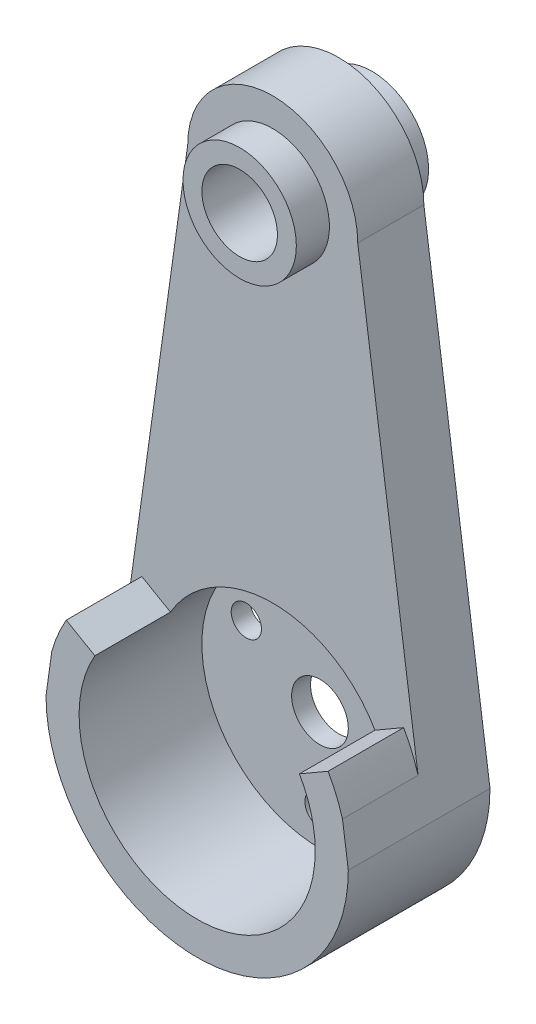
SolidWorks part; units mm, degrees
ref_plane "Plan de face" through (0, 0, 0) normal (0, 0, 1) x (1, 0, 0)
ref_plane "Plan de dessus" through (0, 0, 0) normal (0, 1, 0) x (1, 0, 0)
ref_plane "Plan de droite" through (0, 0, 0) normal (1, 0, 0) x (0, 0, -1)
sketch "Esquisse1" plane through (0, 0, 0) normal (0, 0, 1) x (1, 0, 0)
  line L0 (-16.3093, 0) -> (24.5372, 0) construction
  line L1 (9, 0) -> (16, -50)
  line L2 (-9, 0) -> (-16, -50)
  line L3 (-16, -50) -> (16, -50) construction
  line L4 (0, 0) -> (0, -50) construction
  arc A0 (-9, 0) -> (9, 0) centre (0, 0) cw
  arc A1 (-16, -50) -> (16, -50) centre (0, -50) ccw
  dimension "D1" = 9
  dimension "D2" = 16
  dimension "D3" = 50
extrude "Boss.-Extru.1" add sketch "Esquisse1" along normal blind 7
sketch "Esquisse2" plane through (0, 0, 7) normal (0, 0, 1) x (1, 0, 0)
  line L0 (0, 0) -> (0, -66) construction
  line L1 (16, -50) -> (-16, -50) construction
  circle A0 centre (0, -50) radius 3
  arc A1 (-16, -50) -> (16, -50) centre (0, -50) ccw construction
  dimension "D1" = 6
extrude "Enlèv. mat.-Extru.1" cut sketch "Esquisse2" against normal blind 7
sketch "Esquisse3" plane through (0, 0, 7) normal (0, 0, 1) x (1, 0, 0)
  line L0 (0, -50) -> (0, 0) construction
  line L1 (0, -50) -> (7.7942, -45.5) construction
  line L2 (0, -50) -> (-7.7942, -45.5) construction
  line L3 (0, -50) -> (0, -59) construction
  circle A3 centre (0, -59) radius 1.6
  circle A4 centre (-7.7942, -45.5) radius 1.6
  circle A5 centre (7.7942, -45.5) radius 1.6
  dimension "D5" = 9
  dimension "D6" = 9
extrude "Enlèv. mat.-Extru.2" cut sketch "Esquisse3" against normal blind 7
ref_plane "Plan1" through (0, 10, 0) normal (0, 1, 0) x (1, 0, 0)
sketch "Esquisse5" plane through (0, 0, 7) normal (0, 0, 1) x (1, 0, 0)
  circle A0 centre (0, -50) radius 12.5
  dimension "D1" = 25
extrude "Enlèv. mat.-Extru.5" cut sketch "Esquisse5" against normal blind 5
sketch "Esquisse16" plane through (0, 0, 0) normal (0, 0, -1) x (-1, 0, 0)
  circle A0 centre (0, 0) radius 6
  circle A1 centre (0, 0) radius 4
extrude "Boss.-Extru.5" add sketch "Esquisse16" along normal blind 3.5
sketch "Esquisse17" plane through (0, 0, 7) normal (0, 0, 1) x (1, 0, 0)
  circle A0 centre (0, 0) radius 4
  circle A1 centre (0, 0) radius 6
extrude "Boss.-Extru.6" add sketch "Esquisse17" along normal blind 3.5
sketch "Esquisse18" plane through (0, 0, 7) normal (0, 0, 1) x (1, 0, 0)
  line L0 (0, -50) -> (-13.8564, -42) construction
  line L1 (0, -50) -> (13.8564, -42) construction
  line L2 (-13.8564, -42) -> (-10.8253, -43.75)
  line L3 (10.8253, -43.75) -> (13.8564, -42)
  circle A0 centre (0, -50) radius 12.5
  circle A1 centre (0, -50) radius 16
  circle M2 centre (0, -50) radius 12.5
  line M4 (-9, 0) -> (-16, -50)
  arc M5 (-16, -50) -> (16, -50) centre (0, -50) ccw
  line M6 (16, -50) -> (9, 0)
  dimension "D1" = 120
extrude "Boss.-Extru.8" add sketch "Esquisse18" along normal blind 8 contours A1 L3 L2 M6 M2 M4 M5
sketch "Esquisse19" plane through (0, 0, 7) normal (0, 0, 1) x (1, 0, 0)
  circle A0 centre (0, 0) radius 4
extrude "Enlèv. mat.-Extru.6" cut sketch "Esquisse19" against normal blind 8
